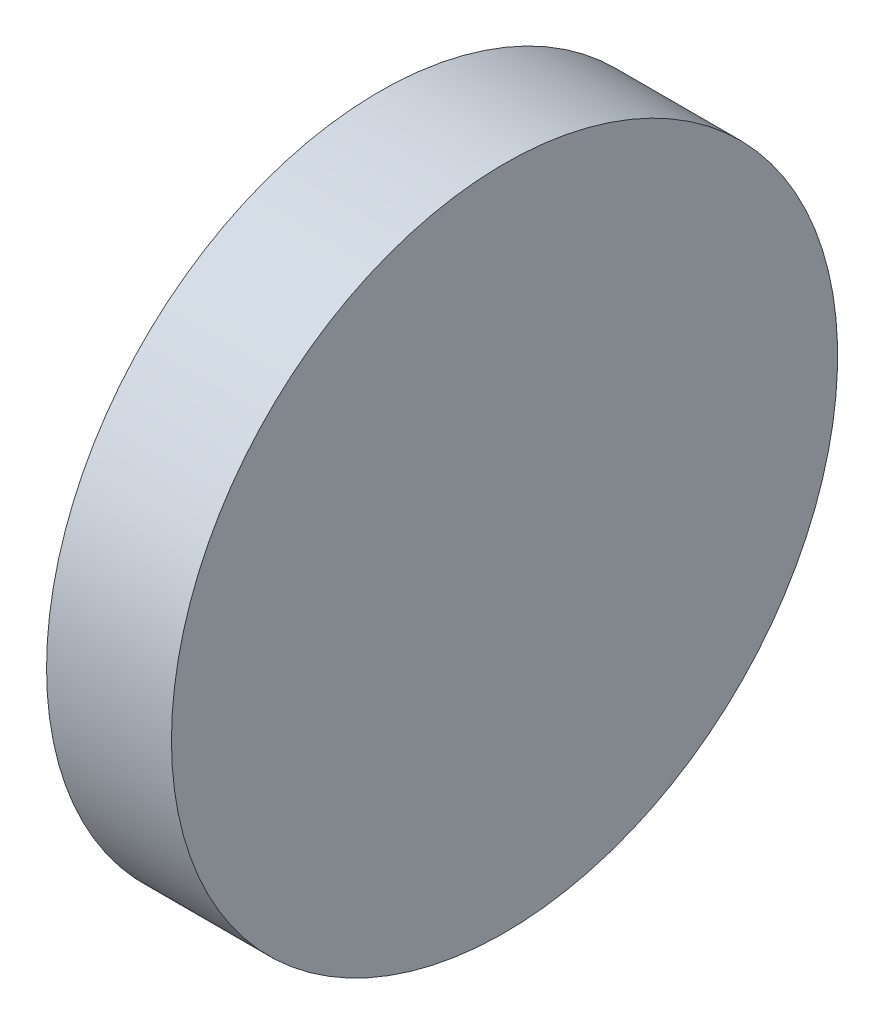
SolidWorks part; units mm, degrees
ref_plane "Front Plane" through (0, 0, 0) normal (0, 0, 1) x (1, 0, 0)
ref_plane "Top Plane" through (0, 0, 0) normal (0, 1, 0) x (1, 0, 0)
ref_plane "Right Plane" through (0, 0, 0) normal (1, 0, 0) x (0, 0, -1)
sketch "Sketch1" plane through (0, 0, 0) normal (1, 0, 0) x (0, 0, -1)
  circle A0 centre (0, 0) radius 12.7
  dimension "D1" = 25.4
extrude "Boss-Extrude1" add sketch "Sketch1" along normal blind 4.7625
